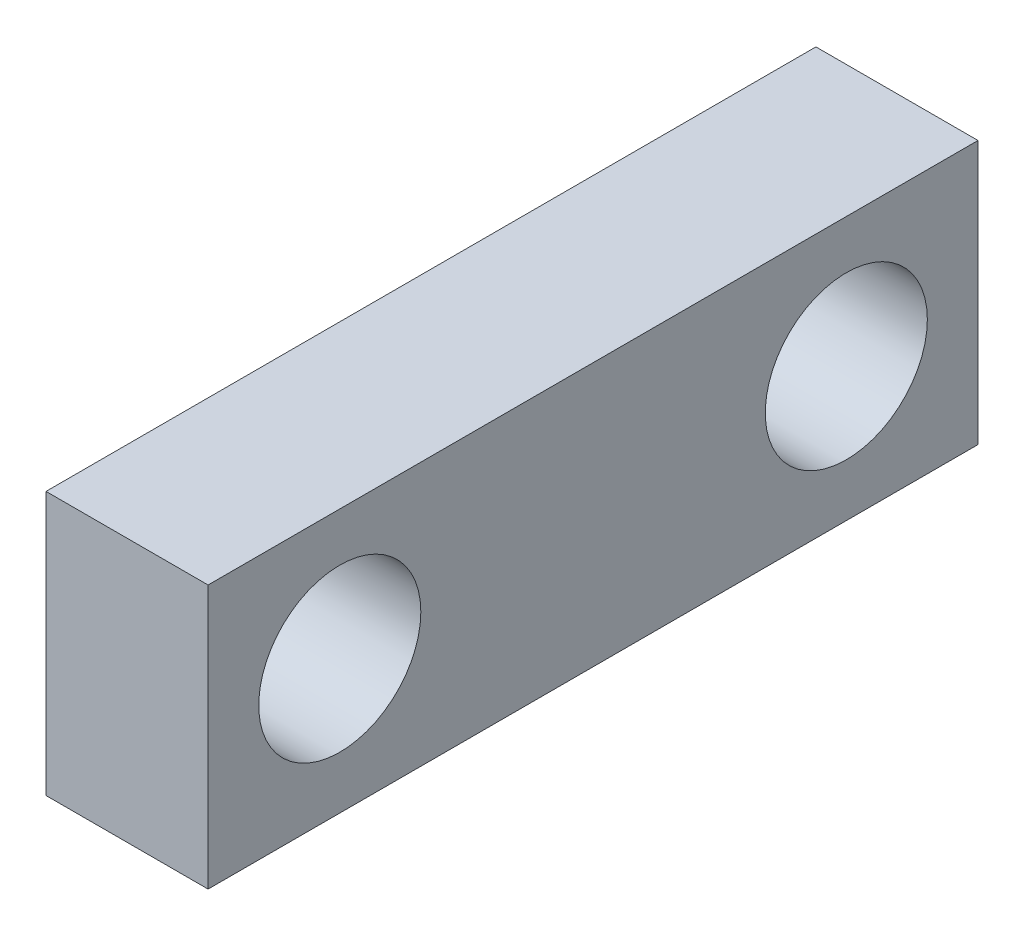
SolidWorks part; units mm, degrees
ref_plane "Front Plane" through (0, 0, 0) normal (0, 0, 1) x (1, 0, 0)
ref_plane "Top Plane" through (0, 0, 0) normal (0, 1, 0) x (1, 0, 0)
ref_plane "Right Plane" through (0, 0, 0) normal (1, 0, 0) x (0, 0, -1)
ref_plane "Plane1" through (18, 0, 0) normal (1, 0, 0) x (0, 0, -1)
sketch "Sketch1" plane through (0, 0, 0) normal (1, 0, 0) x (0, 0, -1)
  line L1 (-484.4065, 53.9437) -> (-446.4065, 53.9437)
  line L2 (-484.4065, 53.9437) -> (-484.4065, 40.9437)
  line L3 (-484.4065, 40.9437) -> (-446.4065, 40.9437)
  line L4 (-446.4065, 53.9437) -> (-446.4065, 40.9437)
  circle A0 centre (-477.9065, 47.5437) radius 4
  circle A1 centre (-452.9065, 47.5437) radius 4
  dimension "D5" = 8
  dimension "D6" = 8
  dimension "D1" = 38
  dimension "D2" = 6.5
  dimension "D3" = 13
  dimension "D4" = 6.4
extrude "Boss-Extrude1" add sketch "Sketch1" along normal blind 8
